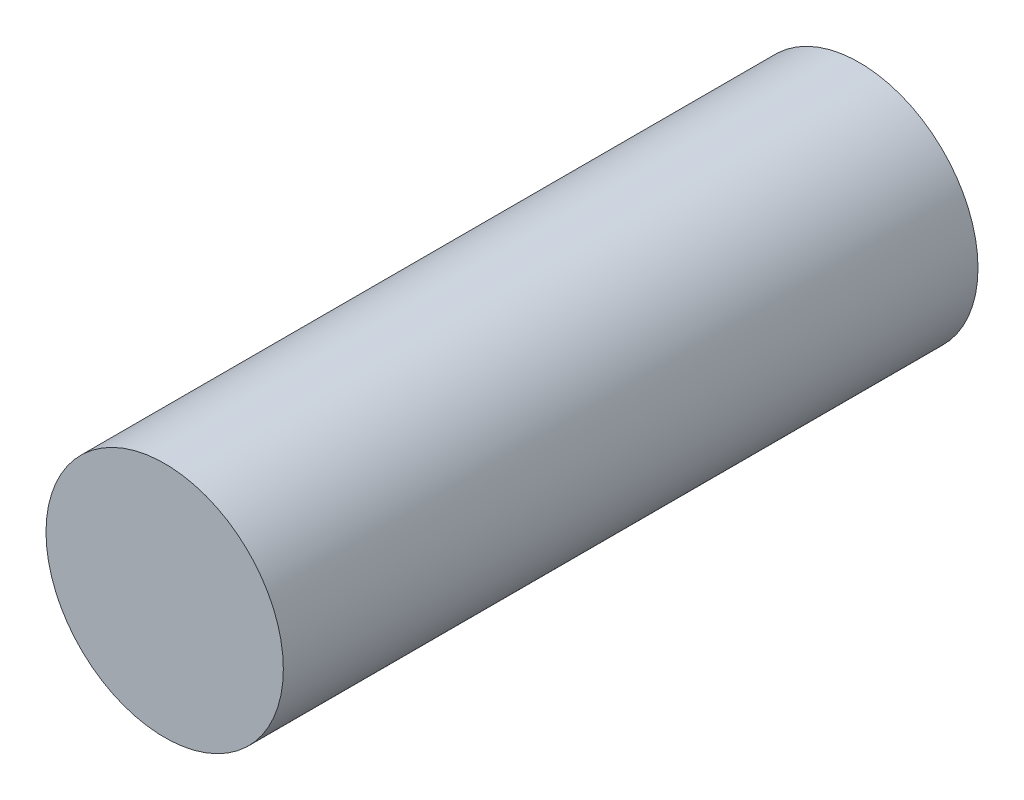
SolidWorks part; units mm, degrees
ref_plane "前视基准面" through (0, 0, 0) normal (0, 0, 1) x (1, 0, 0)
ref_plane "上视基准面" through (0, 0, 0) normal (0, 1, 0) x (1, 0, 0)
ref_plane "右视基准面" through (0, 0, 0) normal (1, 0, 0) x (0, 0, -1)
other "Configuration Table"
sketch "草图1" plane through (0, 0, 0) normal (0, 0, 1) x (1, 0, 0)
  line L0 (-33, -28) -> (33, -28)
  line L1 (33, -28) -> (33, 28)
  line L2 (33, 28) -> (-33, 28)
  line L3 (-33, 28) -> (-33, -28)
extrude "凸台-拉伸1" add sketch "草图1" along normal blind 24
sketch "草图2" plane through (0, 0, 24) normal (0, 0, 1) x (1, 0, 0)
  circle A0 centre (0, -1) radius 4.1
extrude "切除-拉伸1" cut sketch "草图2" against normal through all flip side to cut
